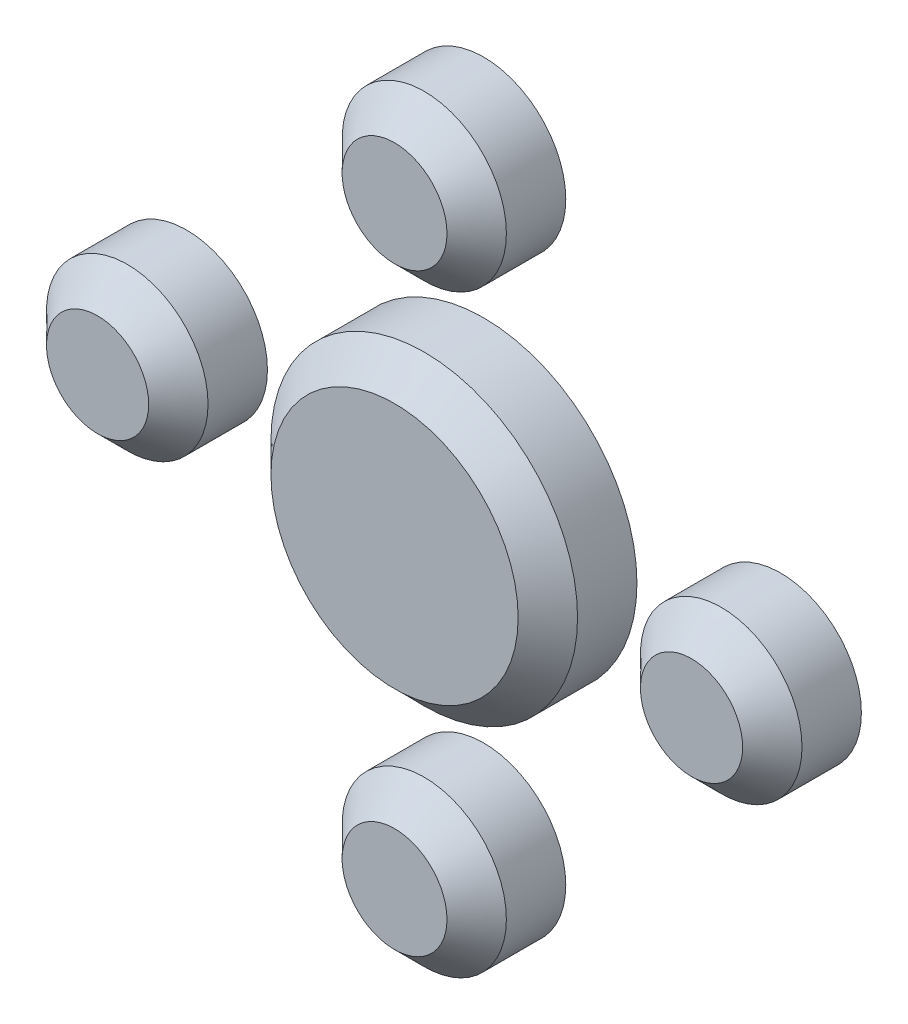
SolidWorks part; units mm, degrees
ref_plane "Front Plane" through (0, 0, 0) normal (0, 0, 1) x (1, 0, 0)
ref_plane "Top Plane" through (0, 0, 0) normal (0, 1, 0) x (1, 0, 0)
ref_plane "Right Plane" through (0, 0, 0) normal (1, 0, 0) x (0, 0, -1)
sketch "Sketch1" plane through (0, 0, 0) normal (0, 0, 1) x (1, 0, 0)
  line L0 (0, 0) -> (-1.8369, 0)
  line L1 (0, 0) -> (0, 2.9582)
  circle A0 centre (0, 0) radius 15
  circle A1 centre (0, 0) radius 5.162
  circle A2 centre (0, 10) radius 2.7654
  circle A3 centre (0, -10) radius 2.7654
  circle A4 centre (-10, 0) radius 2.7199
  circle A5 centre (10, 0) radius 2.7199
  dimension "D1" = 30
  dimension "D2" = 10
  dimension "D3" = 10
extrude "Boss-Extrude1" add sketch "Sketch1" along normal blind 3
chamfer "Chamfer2" distance 1 angle 45 1 edges at (2.7654, 10, 3)
chamfer "Chamfer3" distance 1 angle 45 1 edges at (12.7199, 0, 3)
chamfer "Chamfer4" distance 1 angle 45 1 edges at (-7.2801, 0, 3)
chamfer "Chamfer5" distance 1 angle 45 1 edges at (2.7654, -10, 3)
chamfer "Chamfer6" distance 1 angle 45 1 edges at (5.162, 0, 3)
